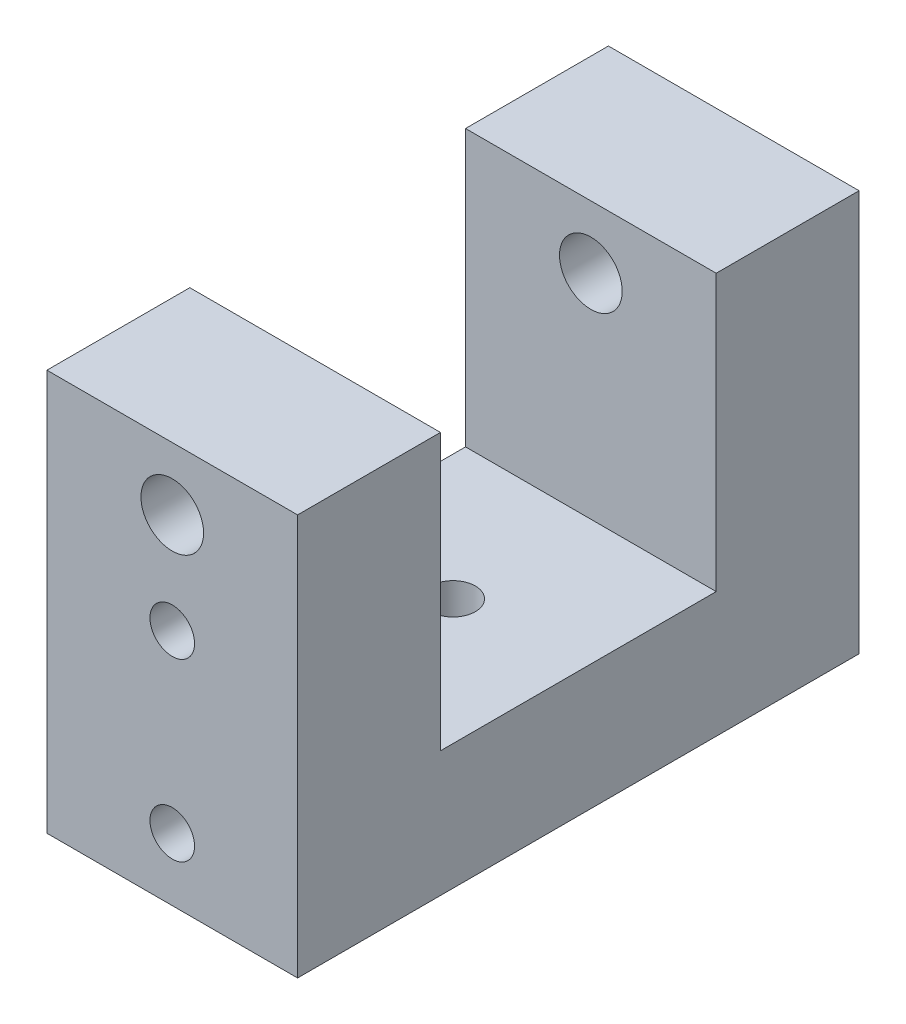
SolidWorks part; units mm, degrees
material "6061-T6 (SS)"
ref_plane "Front Plane" through (0, 0, 0) normal (0, 0, 1) x (1, 0, 0)
ref_plane "Top Plane" through (0, 0, 0) normal (0, 1, 0) x (1, 0, 0)
ref_plane "Right Plane" through (0, 0, 0) normal (1, 0, 0) x (0, 0, -1)
sketch "Sketch1" plane through (0, 0, 0) normal (0, 1, 0) x (1, 0, 0)
  line L1 (-6.35, -14.224) -> (6.35, -14.224)
  line L2 (-6.35, -14.224) -> (-6.35, 14.224)
  line L3 (-6.35, 14.224) -> (6.35, 14.224)
  line L4 (6.35, -14.224) -> (6.35, 14.224)
  line L5 (-6.35, -14.224) -> (6.35, 14.224) construction
  line L6 (-6.35, 14.224) -> (6.35, -14.224) construction
  point P0 (0, 0)
  dimension "D1" = 12.7
  dimension "D2" = 28.448
extrude "Boss-Extrude1" add sketch "Sketch1" along normal blind 20.32
sketch "Sketch2" plane through (6.35, 0, 0) normal (1, 0, 0) x (0, 0, -1)
  line L0 (0, 20.32) -> (0, 0) construction
  line L1 (-14.224, 20.32) -> (14.224, 20.32) construction
  line L2 (-14.224, 0) -> (14.224, 0) construction
  line L3 (-6.985, 6.35) -> (6.985, 6.35)
  line L4 (-6.985, 6.35) -> (-6.985, 20.32)
  line L5 (-6.985, 20.32) -> (6.985, 20.32)
  line L6 (6.985, 6.35) -> (6.985, 20.32)
  line L7 (-6.985, 6.35) -> (6.985, 20.32) construction
  line L8 (-6.985, 20.32) -> (6.985, 6.35) construction
  point P5 (0, 13.335)
  dimension "D1" = 6.35
  dimension "D2" = 13.97
extrude "Cut-Extrude1" cut sketch "Sketch2" against normal through all
sketch "Sketch5" plane through (0, 0, 14.224) normal (0, 0, 1) x (1, 0, 0)
  line L0 (0, 20.32) -> (0, 0) construction
  line L1 (-6.35, 20.32) -> (6.35, 20.32) construction
  line L2 (-6.35, 0) -> (6.35, 0) construction
  circle A0 centre (0, 17.145) radius 1.5875
  dimension "D1" = 3.175
  dimension "D2" = 3.175
extrude "Cut-Extrude2" cut sketch "Sketch5" against normal through all
hole_wizard "#4-40 Tapped Hole1" positions "Sketch7" profile "Sketch8" tap size "#4-40" standard "Progressive" end condition up to next
sketch "Sketch7" plane through (0, 0, 0) normal (0, -1, 0) x (-1, 0, 0)
  point P0 (0, 0)
sketch "Sketch8" plane through (0, 0, 0) normal (1, 0, 0) x (0, 0, -1)
  line L0 (0, 0) -> (0, 6.35)
  line L1 (0, 6.35) -> (1.1303, 6.35)
  line L2 (1.1303, 6.35) -> (1.1303, 0)
  line L5 (1.1303, 0) -> (0, 0)
  line L11 (0, -6.35) -> (0, 107.95) construction
  dimension "Thru Tap Drill Dia." = 2.2606
  dimension "Thru Tap Drill Depth" = 6.35
cosmetic thread "Hole Thread1" parameters "D2"=2.8448
hole_wizard "#4-40 Tapped Hole2" positions "Sketch10" profile "Sketch9" tap size "#4-40" standard "Progressive"
sketch "Sketch10" plane through (0, 0, -14.224) normal (0, 0, -1) x (-1, 0, 0)
  line L0 (0, 20.32) -> (0, 0) construction
  line L1 (-6.35, 20.32) -> (6.35, 20.32) construction
  line L2 (-6.35, 0) -> (6.35, 0) construction
  point P9 (0, 12.065)
  point P11 (0, 3.175)
  dimension "D1" = 3.175
  dimension "D2" = 8.89
sketch "Sketch9" plane through (0, 12.065, -14.224) normal (1, 0, 0) x (0, 1, 0)
  line L0 (0, 0) -> (0, 7.0292)
  line L1 (0, 7.0292) -> (1.1303, 6.35)
  line L2 (1.1303, 6.35) -> (1.1303, 0)
  line L5 (1.1303, 0) -> (0, 0)
  line L10 (0, 7.0292) -> (-1.1303, 6.35) construction
  line L11 (0, -6.35) -> (0, 107.95) construction
  dimension "Tap Drill Dia." = 2.2606
  dimension "Tap Drill Depth" = 6.35
  dimension "Drill Angle" = 118
cosmetic thread "Hole Thread2" parameters "D1"=5.588, "D2"=2.8448
cosmetic thread "Hole Thread3" parameters "D1"=5.588, "D2"=2.8448
hole_wizard "#4-40 Tapped Hole3" positions "Sketch12" profile "Sketch11" tap size "#4-40" standard "Progressive"
sketch "Sketch12" plane through (0, 0, 14.224) normal (0, 0, 1) x (1, 0, 0)
  line L0 (0, 20.32) -> (0, 0) construction
  line L1 (-6.35, 20.32) -> (6.35, 20.32) construction
  line L2 (-6.35, 0) -> (6.35, 0) construction
  point P9 (0, 12.065)
  point P11 (0, 3.175)
  dimension "D1" = 3.175
  dimension "D2" = 8.89
sketch "Sketch11" plane through (0, 12.065, 14.224) normal (1, 0, 0) x (0, -1, 0)
  line L0 (0, 0) -> (0, 7.0292)
  line L1 (0, 7.0292) -> (1.1303, 6.35)
  line L2 (1.1303, 6.35) -> (1.1303, 0)
  line L5 (1.1303, 0) -> (0, 0)
  line L10 (0, 7.0292) -> (-1.1303, 6.35) construction
  line L11 (0, -6.35) -> (0, 107.95) construction
  dimension "Tap Drill Dia." = 2.2606
  dimension "Tap Drill Depth" = 6.35
  dimension "Drill Angle" = 118
cosmetic thread "Hole Thread4" parameters "D1"=5.588, "D2"=2.8448
cosmetic thread "Hole Thread5" parameters "D1"=5.588, "D2"=2.8448
